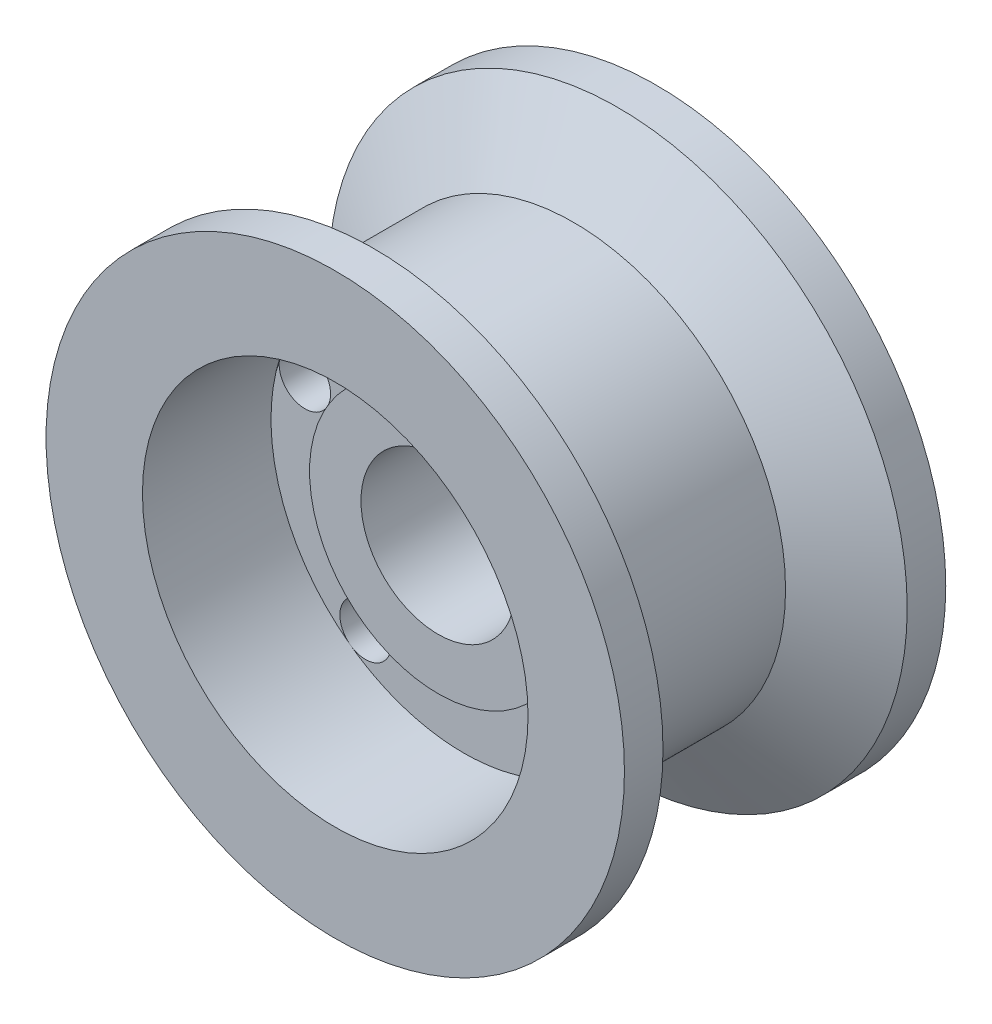
SolidWorks part; units mm, degrees
ref_plane "Front Plane" through (0, 0, 0) normal (0, 0, 1) x (1, 0, 0)
ref_plane "Top Plane" through (0, 0, 0) normal (0, 1, 0) x (1, 0, 0)
ref_plane "Right Plane" through (0, 0, 0) normal (1, 0, 0) x (0, 0, -1)
sketch "Sketch1" plane through (0, 0, 0) normal (0, 0, 1) x (1, 0, 0)
  circle A0 centre (0, 0) radius 22.5
  dimension "D1" = 45
extrude "Boss-Extrude2" add sketch "Sketch1" along normal mid plane 25 contours A0
sketch "Sketch2" plane through (0, 0, 12.5) normal (0, 0, 1) x (1, 0, 0)
  circle A0 centre (0, 0) radius 10
  dimension "D1" = 20
extrude "Cut-Extrude1" cut sketch "Sketch2" against normal through all contours A0
sketch "Sketch3" plane through (0, 0, 12.5) normal (0, 0, 1) x (1, 0, 0)
  circle A0 centre (0, 0) radius 15
  dimension "D1" = 30
extrude "Cut-Extrude2" cut sketch "Sketch3" against normal blind 10 contours A0
mirror "Mirror1" about plane through (0, 0, 0) normal (0, 0, 1) of "Cut-Extrude2"
sketch "Sketch4" plane through (0, 0, 2.5) normal (0, 0, 1) x (1, 0, 0)
  circle A0 centre (0, 13) radius 2
  dimension "D1" = 4
  dimension "D2" = 13
extrude "Cut-Extrude3" cut sketch "Sketch4" against normal through all
pattern_circular "CirPattern1" count 5 over 360 about axis through (0, 0, 0) along (0, 0, 1) of "Cut-Extrude3"
sketch "Sketch5" plane through (0, 0, 0) normal (0, 1, 0) x (1, 0, 0)
  line L0 (22.5, 9.5) -> (22.5, -9.5)
  line L1 (22.5, 9.5) -> (16.5, 6.0359)
  line L2 (22.5, -12.5) -> (22.5, 12.5) construction
  line L3 (16.5, 6.0359) -> (16.5, -6.0359)
  line L4 (16.5, -6.0359) -> (22.5, -9.5)
  line L5 (22.5, 12.5) -> (22.5, -12.5) construction
  line L8 (22.5, 12.5) -> (-22.5, 12.5) construction
  line L9 (-22.5, -12.5) -> (22.5, -12.5) construction
  line L11 (0, -18.2201) -> (0, 19.5389) construction
  dimension "D1" = 6
  dimension "D2" = 3
  dimension "D3" = 3
  dimension "D4" = 60
  dimension "D5" = 60
  dimension "D6" = 12.0718
revolve "Cut-Revolve1" cut sketch "Sketch5" angle 360 about L11
sketch "Sketch6" plane through (0, 0, 2.5) normal (0, 0, 1) x (1, 0, 0)
  circle A0 centre (0, 0) radius 6
  circle A3 centre (0, 0) radius 10 construction
  circle A4 centre (0, 0) radius 10
  dimension "D1" = 12
extrude "Boss-Extrude3" add sketch "Sketch6" along normal blind 2 and the other way blind 7
